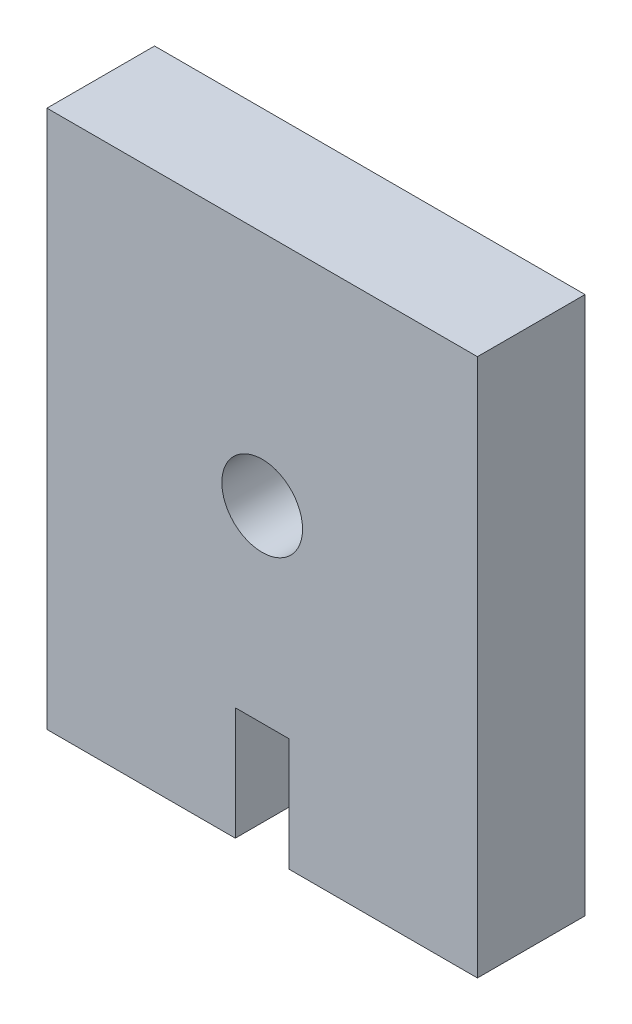
SolidWorks part; units mm, degrees
ref_plane "Front Plane" through (0, 0, 0) normal (0, 0, 1) x (1, 0, 0)
ref_plane "Top Plane" through (0, 0, 0) normal (0, 1, 0) x (1, 0, 0)
ref_plane "Right Plane" through (0, 0, 0) normal (1, 0, 0) x (0, 0, -1)
sketch "Sketch1" plane through (0, 0, 0) normal (0, 0, 1) x (1, 0, 0)
  line L0 (0, 60) -> (0, -80) construction
  line L2 (-80, 80) -> (80, 80)
  line L3 (-80, 80) -> (-80, -120)
  line L4 (-80, -120) -> (80, -120)
  line L5 (80, 80) -> (80, -120)
  circle A0 centre (0, 0) radius 60 construction
  circle A1 centre (0, -80) radius 20 construction
  point P11 (0, 80)
  dimension "D1" = 120
  dimension "D2" = 40
  dimension "D3" = 200
  dimension "D4" = 120
  dimension "D5" = 160
  dimension "D6" = 80
extrude "Boss-Extrude1" add sketch "Sketch1" along normal blind 40
sketch "Sketch2" plane through (0, -120, 0) normal (0, -1, 0) x (1, 0, 0)
  line L0 (0, 0) -> (0, 40) construction
  line L1 (-80, 40) -> (80, 40) construction
  line L3 (-10, 40) -> (10, 40)
  line L4 (-10, 40) -> (-10, 11)
  line L5 (-10, 11) -> (10, 11)
  line L6 (10, 40) -> (10, 11)
  point P9 (0, 11)
  dimension "D1" = 29
  dimension "D2" = 20
extrude "Cut-Extrude1" cut sketch "Sketch2" against normal blind 42
sketch "Sketch3" plane through (0, 0, 40) normal (0, 0, 1) x (1, 0, 0)
  circle A0 centre (0, -8) radius 15
  dimension "D1" = 30
  dimension "D2" = 8
extrude "Cut-Extrude2" cut sketch "Sketch3" against normal blind 25
